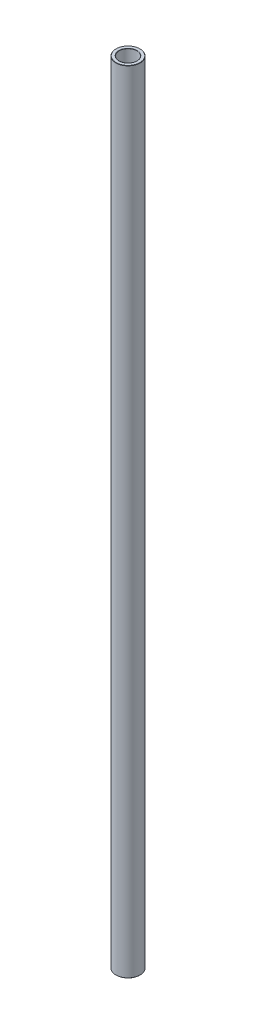
SolidWorks part; units mm, degrees
ref_plane "Front Plane" through (0, 0, 0) normal (0, 0, 1) x (1, 0, 0)
ref_plane "Top Plane" through (0, 0, 0) normal (0, 1, 0) x (1, 0, 0)
ref_plane "Right Plane" through (0, 0, 0) normal (1, 0, 0) x (0, 0, -1)
sketch "Sketch1" plane through (0, 0, 0) normal (0, 1, 0) x (1, 0, 0)
  circle A0 centre (0, 0) radius 12.7
  circle A1 centre (0, 0) radius 9.271
  dimension "D1" = 25.4
  dimension "D2" = 18.542
extrude "Boss-Extrude1" add sketch "Sketch1" along normal blind 827.62 contours A1 | A0
chamfer "Chamfer1" distance 0.254 angle 45 2 edges at (0, 0, 12.7) (0, 827.62, 12.7)
fillet "Fillet1" radius 0.254 2 edges at (0, 0, 9.271) (0, 827.62, 9.271)
